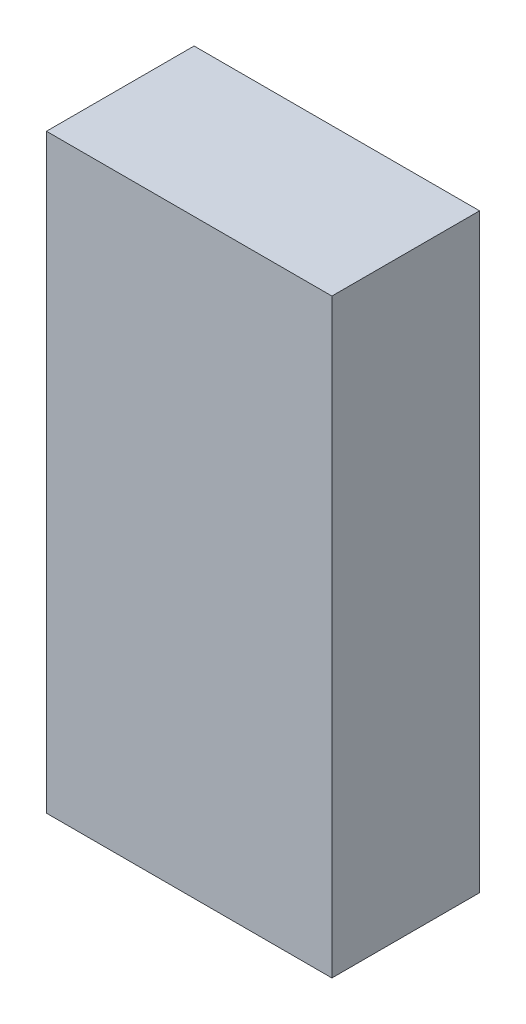
SolidWorks part; units mm, degrees
ref_plane "正面" through (0, 0, 0) normal (0, 0, 1) x (1, 0, 0)
ref_plane "平面" through (0, 0, 0) normal (0, 1, 0) x (1, 0, 0)
ref_plane "右側面" through (0, 0, 0) normal (1, 0, 0) x (0, 0, -1)
sketch "ｽｹｯﾁ2" plane through (0, 0, 0) normal (0, 1, 0) x (1, 0, 0)
  line L1 (0, 0) -> (870, 0)
  line L2 (0, 0) -> (0, 450)
  line L3 (0, 450) -> (870, 450)
  line L4 (870, 0) -> (870, 450)
  dimension "D1" = 870
  dimension "D2" = 450
extrude "ﾎﾞｽ - 押し出し1" add sketch "ｽｹｯﾁ2" along normal blind 1800
